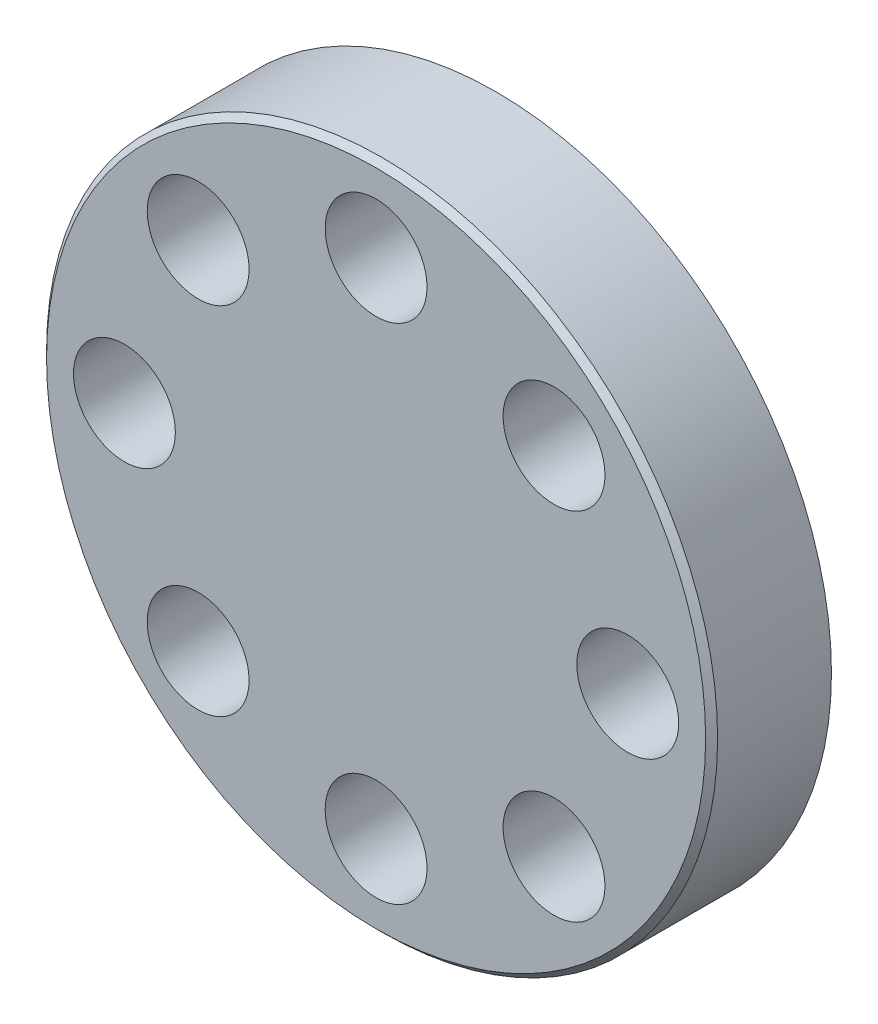
SolidWorks part; units mm, degrees
ref_plane "Piano frontale" through (0, 0, 0) normal (0, 0, 1) x (1, 0, 0)
ref_plane "Piano superiore" through (0, 0, 0) normal (0, 1, 0) x (1, 0, 0)
ref_plane "Piano destro" through (0, 0, 0) normal (1, 0, 0) x (0, 0, -1)
sketch "Schizzo1" plane through (0, 0, 0) normal (0, 0, 1) x (1, 0, 0)
  circle A0 centre (0, 0) radius 10
  dimension "D1" = 20
extrude "Estrusione-Estrusione1" add sketch "Schizzo1" along normal blind 10
sketch "Schizzo2" plane through (0, 0, 10) normal (0, 0, 1) x (1, 0, 0)
  circle A0 centre (0, 0) radius 28
  dimension "D1" = 56
extrude "Estrusione-Estrusione2" add sketch "Schizzo2" along normal blind 10
sketch "Schizzo3" plane through (0, 0, 20) normal (0, 0, 1) x (1, 0, 0)
  circle A0 centre (0, 0) radius 21 construction
  circle A1 centre (0, 21) radius 4.25
  dimension "D1" = 42
  dimension "D2" = 8.5
extrude "Taglio-Estrusione1" cut sketch "Schizzo3" against normal through all
pattern_circular "RipetizioneCircolare1" count 8 over 360 about axis through (0, 0, 0) along (0, 0, 1) of "Taglio-Estrusione1"
chamfer "Smusso1" distance 0.5 angle 45 1 edges at (10, 0, 0)
chamfer "Smusso2" distance 0.5 angle 45 1 edges at (28, 0, 20)
